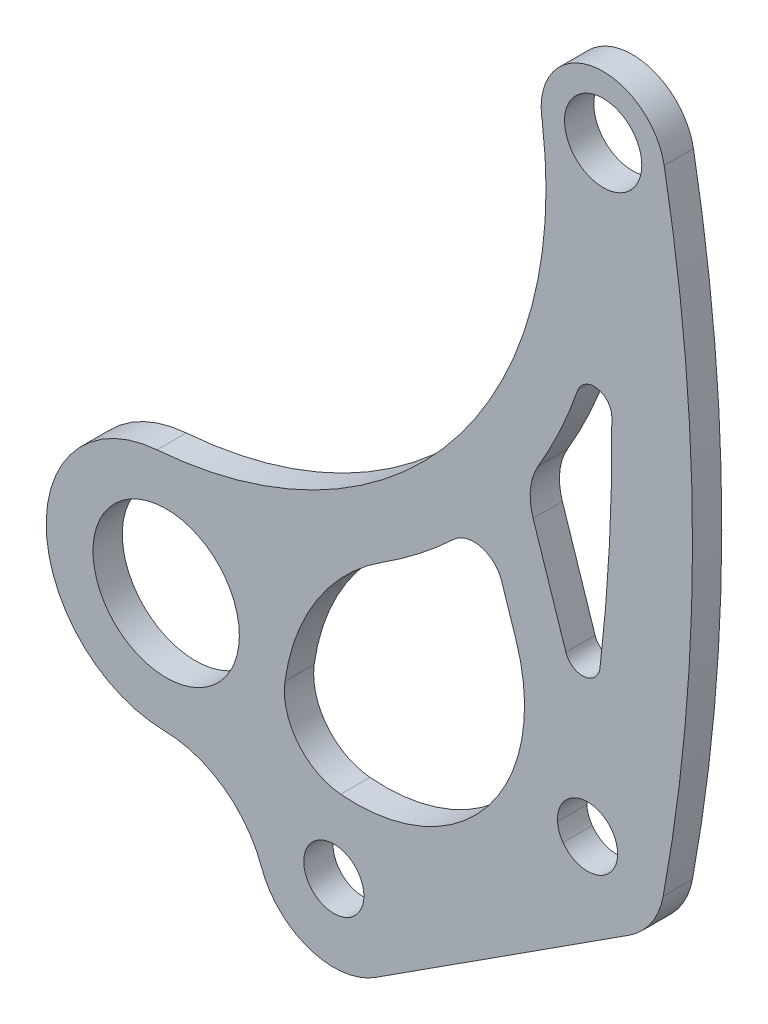
SolidWorks part; units mm, degrees
material "6061-T6 (SS)"
ref_plane "Front Plane" through (0, 0, 0) normal (0, 0, 1) x (1, 0, 0)
ref_plane "Top Plane" through (0, 0, 0) normal (0, 1, 0) x (1, 0, 0)
ref_plane "Right Plane" through (0, 0, 0) normal (1, 0, 0) x (0, 0, -1)
sketch "Sketch2" plane through (0, 0, 0) normal (0, 0, 1) x (1, 0, 0)
  line L0 (0, 0) -> (45.72, 0) construction
  line L1 (45.72, 0) -> (47.4133, 66.0183) construction
  line L2 (47.4133, 66.0183) -> (0, 0) construction
  line L3 (-9.9543, 8.3886) -> (42.2663, 70.3558)
  line L4 (54.1443, 66.0101) -> (54.0639, -0.0102)
  line L5 (46.5729, -8.3002) -> (1.3307, -12.9493)
  line L6 (-6.2268, 4.9225) -> (44.1256, 68.6173)
  line L7 (0.8114, -7.8959) -> (46.0536, -3.2468)
  line L8 (48.9813, -0.1295) -> (51.601, 65.852)
  line L9 (0, 0) -> (18.1918, -17.7262) construction
  line L10 (45.72, 0) -> (38.8832, 9.7026) construction
  line L11 (45.72, 0) -> (42.0108, 11.275) construction
  line L12 (45.72, 0) -> (44.9726, 11.8459) construction
  line L13 (47.2407, 59.2895) -> (45.9339, 8.3412)
  line L14 (45.72, 0) -> (36.8585, 26.9366) construction
  line L15 (34.7499, 24.3546) -> (40.5957, 6.585)
  line L16 (38.8824, 29.7758) -> (45.9339, 8.3412)
  line L17 (41.2892, 13.4683) -> (38.6201, 12.5902) construction
  line L18 (41.2892, 13.4683) -> (43.9584, 14.3464) construction
  line L19 (0, 0) -> (18.1918, -17.7262) construction
  line L20 (-7.2141, -10.8357) -> (13.5678, -24.6716)
  line L21 (50.2373, -7.0153) -> (22.7092, -24.7415)
  line L22 (10.645, 7.4925) -> (25.015, -12.9236)
  line L23 (41.2027, 7.0153) -> (13.6745, -10.7109)
  line L26 (237.1837, -665.5499) -> (-723.8072, 270.8428) construction
  circle A0 centre (0, 0) radius 7.9375
  circle A1 centre (45.72, 0) radius 3.2639
  circle A2 centre (47.4133, 66.0183) radius 4.191
  circle A3 centre (0, 0) radius 13.0175
  circle A4 centre (45.72, 0) radius 8.3439
  circle A5 centre (47.4133, 66.0183) radius 6.731
  circle A8 centre (-4.5053, 58.5645) radius 45.72
  circle A9 centre (-4.5053, 58.5645) radius 52.07
  circle A10 centre (-133.3933, 33.155) radius 190.5
  circle A11 centre (-142.1385, 38.656) radius 190.5
  circle A13 centre (18.1918, -17.7262) radius 3.2639
  circle A14 centre (18.1918, -17.7262) radius 8.3439
  point P29 (47.2407, 59.2895)
  point P30 (45.72, 0)
  dimension "D1" = 8.382
  dimension "D2" = 6.5278
  dimension "D3" = 15.875
  dimension "D13" = 381
  dimension "D14" = 381
  dimension "D17" = 91.44
  dimension "D19" = 6.5278
  dimension "2.7" = 45.72
  dimension "D5" = 66.04
  dimension "D6" = 5.08
  dimension "D7" = 2.54
  dimension "D8" = 5.08
  dimension "D9" = 81.28
  dimension "D4" = 54.83
  dimension "D10" = 71.79
  dimension "D11" = 86.39
  dimension "D12" = 6.35
  dimension "D15" = 25.4
  dimension "D18" = 5.08
extrude "Boss-Extrude1" add sketch "Sketch2" along normal blind 3.175 contours A4 L23 L15 | A9 A2 L8 A5 | A9 A5 L8 A2 | A11 A5 A9 A2 | A5 A11 A2 L6 | A2 A11 A5 L6 | A11 A2 A9 A5 | A11 A4 L8 A5 A9 | A5 L8 A4 L4 | A4 A10 A5 L4 | A11 A4 L8 A1 L7 | A11 A1 L8 A4 | L7 A11 A1 A4 | A4 A11 L7 | A11 L7 A1 | A14 L21 A11 L5 L22 | A14 L5 A13 | L5 A14 | A14 L5 L22 L23 | A14 L22 L5 | L5 A11 A4 L7 L23 L22 | A11 L5 A4 | A11 L21 A4 L5 | A14 L5 A3 L20 | A14 L23 L22 L7 A3 L5 | A9 A3 L7 A0 L6 | A3 A9 L6 | L6 A9 A0 A3 | A9 L6 A0 | A9 A0 L7 A3 | A4 L15 L23 L7 | A9 L15 L23 A4 L16 | A3 A9 L13 A5 L6 A8 | A11 A9 A5 | A9 A11 L13 | L23 L7 L22 | A8 A3 L6
ref_plane "Plane2" through (45.72, 0, 0) normal (-0.576, 0.8174, 0) x (0.8174, 0.576, 0)
split line "Split Line2"
ref_plane "Plane3" through (45.72, 0, 0) normal (-0.063, 0.998, 0) x (0.998, 0.063, 0)
split line "Split Line3"
fillet "Fillet1" [suppressed] radius 2.54
fillet "Fillet2" [suppressed] radius 3.81
fillet "Fillet3" radius 1.905 2 edges at (45.9339, 8.3412, 1.5875) (47.5238, 56.5014, 1.5875)
fillet "Fillet4" radius 6.35 1 edges at (38.8824, 29.7758, 1.5875)
sketch "Sketch3" plane through (0, 0, 3.175) normal (0, 0, 1) x (1, 0, 0)
  line L0 (0, 0) -> (18.1918, -17.7262) construction
  line L1 (34.7499, 24.3546) -> (40.585, 6.6176) construction
  line L2 (18.1918, -17.7262) -> (45.72, 0) construction
  circle A0 centre (45.72, 0) radius 8.3439
  circle A1 centre (18.1918, -17.7262) radius 8.3439
  circle A2 centre (0, 0) radius 13.0175
  circle A3 centre (0, 0) radius 7.9375 construction
  circle A4 centre (18.1918, -17.7262) radius 3.2639 construction
  arc A5 (48.3881, 1.88) -> (42.4626, -0.2055) centre (45.72, 0) ccw construction
  circle A7 centre (20.5527, 8.8458) radius 18.3327
  circle A9 centre (19.523, -2.744) radius 6.6973
  circle A11 centre (36.0489, -5.0667) radius 23.3857
  arc A12 (9.8489, 8.5121) -> (34.7499, 24.3546) centre (-4.5053, 58.5645) ccw construction
  line M20 (21.3187, -5.7886) -> (11.0749, -6.8412)
  arc M21 (11.0749, -6.8412) -> (9.8489, 8.5121) centre (0, 0) ccw
  arc M22 (9.8489, 8.5121) -> (34.7499, 24.3546) centre (-4.5053, 58.5645) ccw
  line M23 (34.7499, 24.3546) -> (40.585, 6.6176)
  line M24 (40.585, 6.6176) -> (21.3187, -5.7886)
  dimension "D1" = 5.08
  dimension "D2" = 5.08
  dimension "D3" = 5.08
extrude "Boss-Extrude2" add sketch "Sketch3" against normal blind 3.175 contours A7 M24 M23 | A9 M21 M20 | A9 A11 M20 | A11 A2 M22
sketch "Sketch4" plane through (0, 0, 0) normal (0, 0, 1) x (1, 0, 0)
  line L0 (0, 0) -> (18.1918, -17.7262) construction
  line L1 (34.7499, 24.3546) -> (37.9672, 14.5748) construction
  line L2 (18.1918, -17.7262) -> (45.72, 0) construction
  line L3 (12.8908, -1.8118) -> (38.5393, 5.3003)
  line L4 (38.5393, 5.3003) -> (21.3187, -5.7886) construction
  circle A0 centre (45.72, 0) radius 8.3439
  circle A1 centre (18.1918, -17.7262) radius 8.3439
  circle A2 centre (0, 0) radius 13.0175
  circle A7 centre (20.5527, 8.8458) radius 18.3327
  circle A9 centre (19.523, -2.744) radius 6.6973
  circle A10 centre (0, 0) radius 7.9375 construction
  circle A11 centre (18.1918, -17.7262) radius 3.2639 construction
  arc A12 (48.3881, 1.88) -> (42.4626, -0.2055) centre (45.72, 0) ccw construction
  dimension "D1" = 5.08
  dimension "D2" = 5.08
  dimension "D3" = 5.08
extrude "Cut-Extrude1" cut sketch "Sketch4" along normal blind 12.065 contours A9 A7 L3 | L3 A9
fillet "Fillet5" radius 3.175 1 edges at (34.7499, 24.3546, 1.5875)
sketch "Sketch7" plane through (0, 0, 3.175) normal (0, 0, 1) x (1, 0, 0)
  line L0 (0, 0) -> (18.1918, -17.7262) construction
  line L1 (-30.2621, 20.6214) -> (30.1946, -38.2878) construction
  line L7 (-7.2141, -10.8357) -> (-10.6432, -19.504)
  line L8 (13.5678, -24.6716) -> (10.3391, -28.2385)
  line L9 (-10.6432, -19.504) -> (10.3391, -28.2385)
  circle A0 centre (18.1918, -17.7262) radius 3.2639 construction
  arc A1 (-7.2141, -10.8357) -> (-0.1969, -13.016) centre (0, 0) ccw
  arc A2 (10.3391, -20.5466) -> (13.5678, -24.6716) centre (18.1918, -17.7262) ccw
  arc A3 (13.5678, -24.6716) -> (22.7092, -24.7415) centre (18.1918, -17.7262) ccw construction
  arc A4 (-0.9985, 12.9792) -> (-7.2141, -10.8357) centre (0, 0) ccw construction
  arc A5 (10.3391, -20.5466) -> (-0.1969, -13.016) centre (-0.3691, -24.3926) ccw
  dimension "D1" = 6.35
extrude "Cut-Extrude4" cut sketch "Sketch7" against normal through all
equation "\"Droop angle\"= 54.83"
equation "\"Static angle\"= 71.79"
equation "\"Jounce angle\"= 86.39"
equation "\"D4@Sketch2\"=\"Droop angle\""
equation "\"D10@Sketch2\"=\"Static angle\""
equation "\"D11@Sketch2\"=\"Jounce angle\""
equation "\"DL Rocker Angle\"= 50.124deg"
equation "\"DL Rocker Length\"= 1.0in"
equation "\"D15@Sketch2\"=\"DL Rocker Length\""
